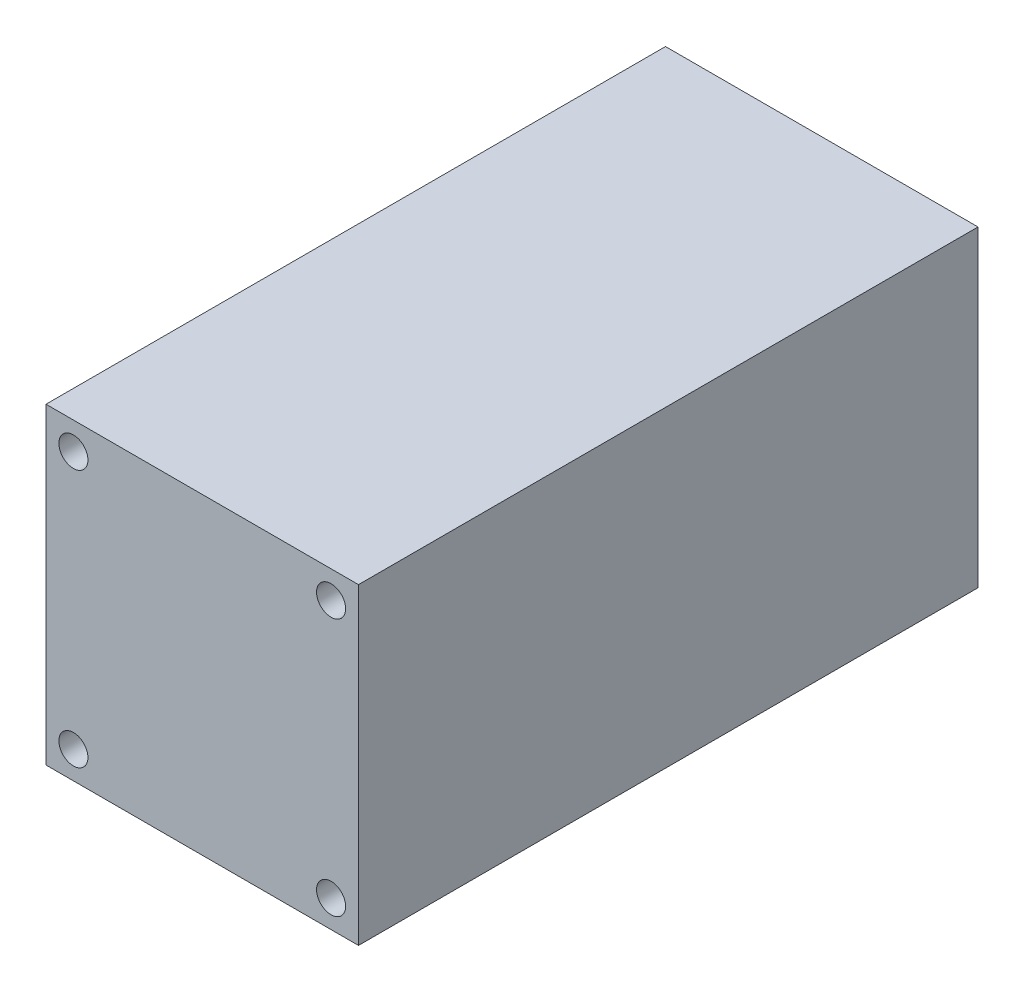
SolidWorks part; units mm, degrees
ref_plane "Front Plane" through (0, 0, 0) normal (0, 0, 1) x (1, 0, 0)
ref_plane "Top Plane" through (0, 0, 0) normal (0, 1, 0) x (1, 0, 0)
ref_plane "Right Plane" through (0, 0, 0) normal (1, 0, 0) x (0, 0, -1)
sketch "Sketch1" plane through (0, 0, 0) normal (0, 0, 1) x (1, 0, 0)
  line L1 (-28.5, -28.5) -> (28.5, -28.5)
  line L2 (-28.5, -28.5) -> (-28.5, 28.5)
  line L3 (-28.5, 28.5) -> (28.5, 28.5)
  line L4 (28.5, -28.5) -> (28.5, 28.5)
  line L5 (-28.5, -28.5) -> (28.5, 28.5) construction
  line L6 (-28.5, 28.5) -> (28.5, -28.5) construction
  line L7 (23.5, -23.5) -> (-23.5, -23.5) construction
  line L8 (23.5, -23.5) -> (23.5, 23.5) construction
  line L9 (23.5, 23.5) -> (-23.5, 23.5) construction
  line L10 (-23.5, -23.5) -> (-23.5, 23.5) construction
  line L11 (23.5, -23.5) -> (-23.5, 23.5) construction
  line L12 (23.5, 23.5) -> (-23.5, -23.5) construction
  circle A0 centre (-23.5, 23.5) radius 2.65
  circle A1 centre (23.5, 23.5) radius 2.65
  circle A2 centre (23.5, -23.5) radius 2.65
  circle A3 centre (-23.5, -23.5) radius 2.65
  point P0 (0, 0)
  point P5 (0, 0)
  dimension "D1" = 57
  dimension "D5" = 5.3
  dimension "D2" = 57
  dimension "D3" = 47
  dimension "D4" = 47
  dimension "D6" = 23.5
  dimension "D7" = 23.5
extrude "Boss-Extrude1" add sketch "Sketch1" along normal blind 113
sketch "Sketch2" plane through (0, 0, 0) normal (0, 0, 1) x (1, 0, 0)
  circle A0 centre (0, 0) radius 19.075
  dimension "D1" = 38.15
extrude "Boss-Extrude2" add sketch "Sketch2" against normal blind 1.6
sketch "Sketch3" plane through (0, 0, 0) normal (0, 0, 1) x (1, 0, 0)
  circle A0 centre (0, 0) radius 5
  dimension "D1" = 10
extrude "Boss-Extrude3" add sketch "Sketch3" against normal blind 22.4
